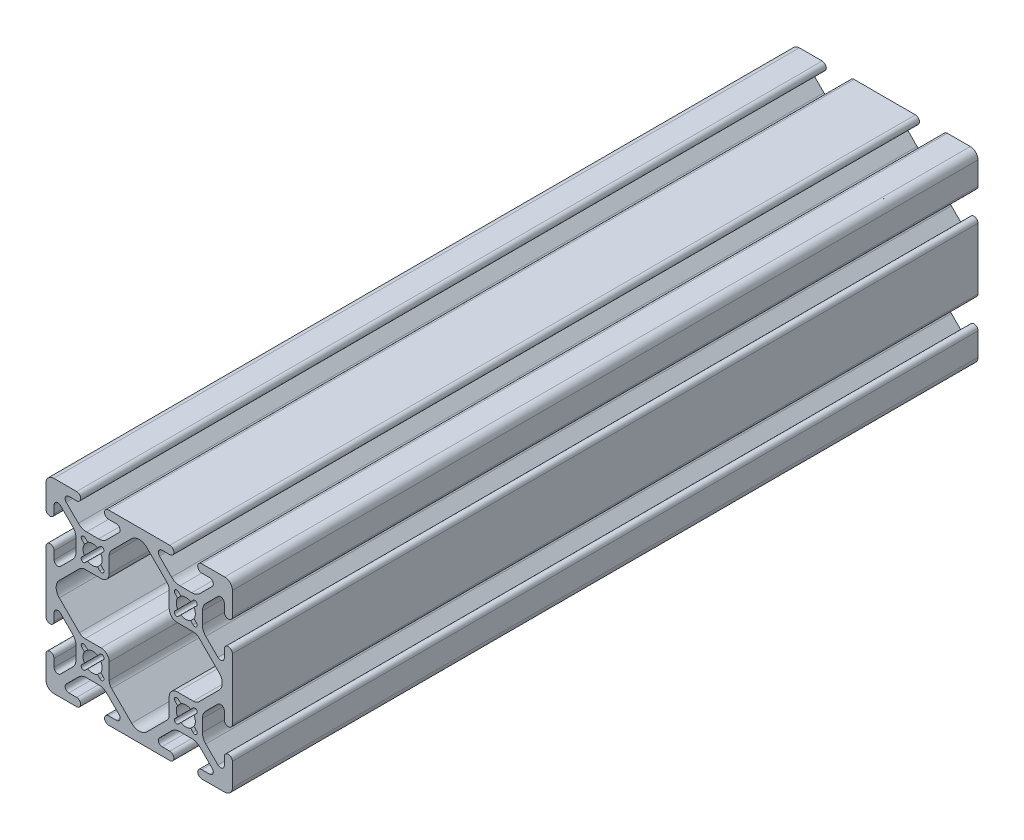
SolidWorks part; units mm, degrees
material "6105-T5 Aluminum"
ref_plane "Front Plane" through (0, 0, 0) normal (0, 0, 1) x (1, 0, 0)
ref_plane "Top Plane" through (0, 0, 0) normal (0, 1, 0) x (1, 0, 0)
ref_plane "Right Plane" through (0, 0, 0) normal (1, 0, 0) x (0, 0, -1)
sketch "Sketch1" plane through (0, 0, 0) normal (0, 0, 1) x (1, 0, 0)
  line L0 (-14.6692, 15.5605) -> (-14.0405, 14.9319)
  line L1 (-11.3595, 14.9319) -> (-10.7308, 15.5605)
  line L2 (-9.8395, 14.6692) -> (-10.4681, 14.0405)
  line L3 (-10.4681, 11.3595) -> (-9.8395, 10.7308)
  line L4 (-10.7308, 9.8395) -> (-11.3595, 10.4681)
  line L5 (-14.0405, 10.4681) -> (-14.6692, 9.8395)
  line L6 (-15.5605, 10.7308) -> (-14.9319, 11.3595)
  line L7 (-14.9319, 14.0405) -> (-15.5605, 14.6692)
  line L8 (11.3595, 10.4681) -> (10.7308, 9.8395)
  line L9 (9.8395, 10.7308) -> (10.4681, 11.3595)
  line L10 (10.4681, 14.0405) -> (9.8395, 14.6692)
  line L11 (10.7308, 15.5605) -> (11.3595, 14.9319)
  line L12 (14.0405, 14.9319) -> (14.6692, 15.5605)
  line L13 (15.5605, 14.6692) -> (14.9319, 14.0405)
  line L14 (14.9319, 11.3595) -> (15.5605, 10.7308)
  line L15 (14.6692, 9.8395) -> (14.0405, 10.4681)
  line L16 (-14.6692, -9.8395) -> (-14.0405, -10.4681)
  line L17 (-11.3595, -10.4681) -> (-10.7308, -9.8395)
  line L18 (-9.8395, -10.7308) -> (-10.4681, -11.3595)
  line L19 (-10.4681, -14.0405) -> (-9.8395, -14.6692)
  line L20 (-10.7308, -15.5605) -> (-11.3595, -14.9319)
  line L21 (-14.0405, -14.9319) -> (-14.6692, -15.5605)
  line L22 (-15.5605, -14.6692) -> (-14.9319, -14.0405)
  line L23 (-14.9319, -11.3595) -> (-15.5605, -10.7308)
  line L24 (10.7308, -9.8395) -> (11.3595, -10.4681)
  line L25 (14.0405, -10.4681) -> (14.6692, -9.8395)
  line L26 (15.5605, -10.7308) -> (14.9319, -11.3595)
  line L27 (14.9319, -14.0405) -> (15.5605, -14.6692)
  line L28 (14.6692, -15.5605) -> (14.0405, -14.9319)
  line L29 (11.3595, -14.9319) -> (10.7308, -15.5605)
  line L30 (9.8395, -14.6692) -> (10.4681, -14.0405)
  line L31 (10.4681, -11.3595) -> (9.8395, -10.7308)
  line L32 (7.5356, -16.3017) -> (2.0587, -21.7787)
  line L33 (-2.0587, -21.7787) -> (-7.5356, -16.3017)
  line L34 (-8.1828, -14.7392) -> (-8.1828, -10.3926)
  line L35 (-10.3926, -8.1828) -> (-14.7392, -8.1828)
  line L36 (-16.3017, -7.5356) -> (-21.7787, -2.0587)
  line L37 (-21.7787, 2.0587) -> (-16.3017, 7.5356)
  line L38 (-14.7392, 8.1828) -> (-10.3926, 8.1828)
  line L39 (-8.1828, 10.3926) -> (-8.1828, 14.7392)
  line L40 (-7.5356, 16.3017) -> (-2.0587, 21.7787)
  line L41 (2.0587, 21.7787) -> (7.5356, 16.3017)
  line L42 (8.1828, 14.7392) -> (8.1828, 10.3926)
  line L43 (10.3926, 8.1828) -> (14.7392, 8.1828)
  line L44 (16.3017, 7.5356) -> (21.7787, 2.0587)
  line L45 (21.7787, -2.0587) -> (16.3017, -7.5356)
  line L46 (14.7392, -8.1828) -> (10.3926, -8.1828)
  line L47 (8.1828, -10.3926) -> (8.1828, -14.7392)
  line L48 (25.4, 17.0561) -> (25.4, 23.2918)
  line L49 (23.2918, 25.4) -> (17.0561, 25.4)
  line L50 (17.0561, 23.1902) -> (19.1749, 23.1902)
  line L51 (19.8933, 21.4558) -> (16.5846, 18.1471)
  line L52 (14.3396, 17.2172) -> (11.0604, 17.2172)
  line L53 (8.8154, 18.1471) -> (5.5067, 21.4558)
  line L54 (6.2251, 23.1902) -> (8.3439, 23.1902)
  line L55 (8.3439, 25.4) -> (-8.3439, 25.4)
  line L56 (-8.3439, 23.1902) -> (-6.2251, 23.1902)
  line L57 (-5.5067, 21.4558) -> (-8.8154, 18.1471)
  line L58 (-11.0604, 17.2172) -> (-14.3396, 17.2172)
  line L59 (-16.5846, 18.1471) -> (-19.8933, 21.4558)
  line L60 (-19.1749, 23.1902) -> (-17.0561, 23.1902)
  line L61 (-17.0561, 25.4) -> (-23.2918, 25.4)
  line L62 (-25.4, 23.2918) -> (-25.4, 17.0561)
  line L63 (-23.1902, 17.0561) -> (-23.1902, 19.1749)
  line L64 (-21.4558, 19.8933) -> (-18.1471, 16.5846)
  line L65 (-17.2172, 14.3396) -> (-17.2172, 11.0604)
  line L66 (-18.1471, 8.8154) -> (-21.4558, 5.5067)
  line L67 (-23.1902, 6.2251) -> (-23.1902, 8.3439)
  line L68 (-25.4, 8.3439) -> (-25.4, -8.3439)
  line L69 (-23.1902, -8.3439) -> (-23.1902, -6.2251)
  line L70 (-21.4558, -5.5067) -> (-18.1471, -8.8154)
  line L71 (-17.2172, -11.0604) -> (-17.2172, -14.3396)
  line L72 (-18.1471, -16.5846) -> (-21.4558, -19.8933)
  line L73 (-23.1902, -19.1749) -> (-23.1902, -17.0561)
  line L74 (-25.4, -17.0561) -> (-25.4, -23.2918)
  line L75 (-23.2918, -25.4) -> (-17.0561, -25.4)
  line L76 (-17.0561, -23.1902) -> (-19.1749, -23.1902)
  line L77 (-19.8933, -21.4558) -> (-16.5846, -18.1471)
  line L78 (-14.3396, -17.2172) -> (-11.0604, -17.2172)
  line L79 (-8.8154, -18.1471) -> (-5.5067, -21.4558)
  line L80 (-6.2251, -23.1902) -> (-8.3439, -23.1902)
  line L81 (-8.3439, -25.4) -> (8.3439, -25.4)
  line L82 (8.3439, -23.1902) -> (6.2251, -23.1902)
  line L83 (5.5067, -21.4558) -> (8.8154, -18.1471)
  line L84 (11.0604, -17.2172) -> (14.3396, -17.2172)
  line L85 (16.5846, -18.1471) -> (19.8933, -21.4558)
  line L86 (19.1749, -23.1902) -> (17.0561, -23.1902)
  line L87 (17.0561, -25.4) -> (23.2918, -25.4)
  line L88 (25.4, -23.2918) -> (25.4, -17.0561)
  line L89 (23.1902, -17.0561) -> (23.1902, -19.1749)
  line L90 (21.4558, -19.8933) -> (18.1471, -16.5846)
  line L91 (17.2172, -14.3396) -> (17.2172, -11.0604)
  line L92 (18.1471, -8.8154) -> (21.4558, -5.5067)
  line L93 (23.1902, -6.2251) -> (23.1902, -8.3439)
  line L94 (25.4, -8.3439) -> (25.4, 8.3439)
  line L95 (23.1902, 8.3439) -> (23.1902, 6.2251)
  line L96 (21.4558, 5.5067) -> (18.1471, 8.8154)
  line L97 (17.2172, 11.0604) -> (17.2172, 14.3396)
  line L98 (18.1471, 16.5846) -> (21.4558, 19.8933)
  line L99 (23.1902, 19.1749) -> (23.1902, 17.0561)
  arc A0 (-11.3595, 14.9319) -> (-14.0405, 14.9319) centre (-12.7, 12.7) ccw
  arc A1 (-9.8395, 14.6692) -> (-10.7308, 15.5605) centre (-10.2304, 15.1696) ccw
  arc A2 (-10.4681, 11.3595) -> (-10.4681, 14.0405) centre (-12.7, 12.7) ccw
  arc A3 (-10.7308, 9.8395) -> (-9.8395, 10.7308) centre (-10.2304, 10.2304) ccw
  arc A4 (-14.0405, 10.4681) -> (-11.3595, 10.4681) centre (-12.7, 12.7) ccw
  arc A5 (-15.5605, 10.7308) -> (-14.6692, 9.8395) centre (-15.1696, 10.2304) ccw
  arc A6 (-14.9319, 14.0405) -> (-14.9319, 11.3595) centre (-12.7, 12.7) ccw
  arc A7 (-14.6692, 15.5605) -> (-15.5605, 14.6692) centre (-15.1696, 15.1696) ccw
  arc A8 (9.8395, 10.7308) -> (10.7308, 9.8395) centre (10.2304, 10.2304) ccw
  arc A9 (10.4681, 14.0405) -> (10.4681, 11.3595) centre (12.7, 12.7) ccw
  arc A10 (10.7308, 15.5605) -> (9.8395, 14.6692) centre (10.2304, 15.1696) ccw
  arc A11 (14.0405, 14.9319) -> (11.3595, 14.9319) centre (12.7, 12.7) ccw
  arc A12 (15.5605, 14.6692) -> (14.6692, 15.5605) centre (15.1696, 15.1696) ccw
  arc A13 (14.9319, 11.3595) -> (14.9319, 14.0405) centre (12.7, 12.7) ccw
  arc A14 (14.6692, 9.8395) -> (15.5605, 10.7308) centre (15.1696, 10.2304) ccw
  arc A15 (11.3595, 10.4681) -> (14.0405, 10.4681) centre (12.7, 12.7) ccw
  arc A16 (-11.3595, -10.4681) -> (-14.0405, -10.4681) centre (-12.7, -12.7) ccw
  arc A17 (-9.8395, -10.7308) -> (-10.7308, -9.8395) centre (-10.2304, -10.2304) ccw
  arc A18 (-10.4681, -14.0405) -> (-10.4681, -11.3595) centre (-12.7, -12.7) ccw
  arc A19 (-10.7308, -15.5605) -> (-9.8395, -14.6692) centre (-10.2304, -15.1696) ccw
  arc A20 (-14.0405, -14.9319) -> (-11.3595, -14.9319) centre (-12.7, -12.7) ccw
  arc A21 (-15.5605, -14.6692) -> (-14.6692, -15.5605) centre (-15.1696, -15.1696) ccw
  arc A22 (-14.9319, -11.3595) -> (-14.9319, -14.0405) centre (-12.7, -12.7) ccw
  arc A23 (-14.6692, -9.8395) -> (-15.5605, -10.7308) centre (-15.1696, -10.2304) ccw
  arc A24 (14.0405, -10.4681) -> (11.3595, -10.4681) centre (12.7, -12.7) ccw
  arc A25 (15.5605, -10.7308) -> (14.6692, -9.8395) centre (15.1696, -10.2304) ccw
  arc A26 (14.9319, -14.0405) -> (14.9319, -11.3595) centre (12.7, -12.7) ccw
  arc A27 (14.6692, -15.5605) -> (15.5605, -14.6692) centre (15.1696, -15.1696) ccw
  arc A28 (11.3595, -14.9319) -> (14.0405, -14.9319) centre (12.7, -12.7) ccw
  arc A29 (9.8395, -14.6692) -> (10.7308, -15.5605) centre (10.2304, -15.1696) ccw
  arc A30 (10.4681, -11.3595) -> (10.4681, -14.0405) centre (12.7, -12.7) ccw
  arc A31 (10.7308, -9.8395) -> (9.8395, -10.7308) centre (10.2304, -10.2304) ccw
  arc A32 (-2.0587, -21.7787) -> (2.0587, -21.7787) centre (0, -19.72) ccw
  arc A33 (-8.1828, -14.7392) -> (-7.5356, -16.3017) centre (-5.973, -14.7392) ccw
  arc A34 (-8.1828, -10.3926) -> (-10.3926, -8.1828) centre (-10.3926, -10.3926) ccw
  arc A35 (-16.3017, -7.5356) -> (-14.7392, -8.1828) centre (-14.7392, -5.973) ccw
  arc A36 (-21.7787, 2.0587) -> (-21.7787, -2.0587) centre (-19.72, 0) ccw
  arc A37 (-14.7392, 8.1828) -> (-16.3017, 7.5356) centre (-14.7392, 5.973) ccw
  arc A38 (-10.3926, 8.1828) -> (-8.1828, 10.3926) centre (-10.3926, 10.3926) ccw
  arc A39 (-7.5356, 16.3017) -> (-8.1828, 14.7392) centre (-5.973, 14.7392) ccw
  arc A40 (2.0587, 21.7787) -> (-2.0587, 21.7787) centre (0, 19.72) ccw
  arc A41 (8.1828, 14.7392) -> (7.5356, 16.3017) centre (5.973, 14.7392) ccw
  arc A42 (8.1828, 10.3926) -> (10.3926, 8.1828) centre (10.3926, 10.3926) ccw
  arc A43 (16.3017, 7.5356) -> (14.7392, 8.1828) centre (14.7392, 5.973) ccw
  arc A44 (21.7787, -2.0587) -> (21.7787, 2.0587) centre (19.72, 0) ccw
  arc A45 (14.7392, -8.1828) -> (16.3017, -7.5356) centre (14.7392, -5.973) ccw
  arc A46 (10.3926, -8.1828) -> (8.1828, -10.3926) centre (10.3926, -10.3926) ccw
  arc A47 (7.5356, -16.3017) -> (8.1828, -14.7392) centre (5.973, -14.7392) ccw
  arc A48 (23.1902, 17.0561) -> (25.4, 17.0561) centre (24.2951, 17.0561) ccw
  arc A49 (25.4, 23.2918) -> (23.2918, 25.4) centre (23.2918, 23.2918) ccw
  arc A50 (17.0561, 25.4) -> (17.0561, 23.1902) centre (17.0561, 24.2951) ccw
  arc A51 (19.8933, 21.4558) -> (19.1749, 23.1902) centre (19.1749, 22.1742) ccw
  arc A52 (14.3396, 17.2172) -> (16.5846, 18.1471) centre (14.3396, 20.3922) ccw
  arc A53 (8.8154, 18.1471) -> (11.0604, 17.2172) centre (11.0604, 20.3922) ccw
  arc A54 (6.2251, 23.1902) -> (5.5067, 21.4558) centre (6.2251, 22.1742) ccw
  arc A55 (8.3439, 23.1902) -> (8.3439, 25.4) centre (8.3439, 24.2951) ccw
  arc A56 (-8.3439, 25.4) -> (-8.3439, 23.1902) centre (-8.3439, 24.2951) ccw
  arc A57 (-5.5067, 21.4558) -> (-6.2251, 23.1902) centre (-6.2251, 22.1742) ccw
  arc A58 (-11.0604, 17.2172) -> (-8.8154, 18.1471) centre (-11.0604, 20.3922) ccw
  arc A59 (-16.5846, 18.1471) -> (-14.3396, 17.2172) centre (-14.3396, 20.3922) ccw
  arc A60 (-19.1749, 23.1902) -> (-19.8933, 21.4558) centre (-19.1749, 22.1742) ccw
  arc A61 (-17.0561, 23.1902) -> (-17.0561, 25.4) centre (-17.0561, 24.2951) ccw
  arc A62 (-23.2918, 25.4) -> (-25.4, 23.2918) centre (-23.2918, 23.2918) ccw
  arc A63 (-25.4, 17.0561) -> (-23.1902, 17.0561) centre (-24.2951, 17.0561) ccw
  arc A64 (-21.4558, 19.8933) -> (-23.1902, 19.1749) centre (-22.1742, 19.1749) ccw
  arc A65 (-17.2172, 14.3396) -> (-18.1471, 16.5846) centre (-20.3922, 14.3396) ccw
  arc A66 (-18.1471, 8.8154) -> (-17.2172, 11.0604) centre (-20.3922, 11.0604) ccw
  arc A67 (-23.1902, 6.2251) -> (-21.4558, 5.5067) centre (-22.1742, 6.2251) ccw
  arc A68 (-23.1902, 8.3439) -> (-25.4, 8.3439) centre (-24.2951, 8.3439) ccw
  arc A69 (-25.4, -8.3439) -> (-23.1902, -8.3439) centre (-24.2951, -8.3439) ccw
  arc A70 (-21.4558, -5.5067) -> (-23.1902, -6.2251) centre (-22.1742, -6.2251) ccw
  arc A71 (-17.2172, -11.0604) -> (-18.1471, -8.8154) centre (-20.3922, -11.0604) ccw
  arc A72 (-18.1471, -16.5846) -> (-17.2172, -14.3396) centre (-20.3922, -14.3396) ccw
  arc A73 (-23.1902, -19.1749) -> (-21.4558, -19.8933) centre (-22.1742, -19.1749) ccw
  arc A74 (-23.1902, -17.0561) -> (-25.4, -17.0561) centre (-24.2951, -17.0561) ccw
  arc A75 (-25.4, -23.2918) -> (-23.2918, -25.4) centre (-23.2918, -23.2918) ccw
  arc A76 (-17.0561, -25.4) -> (-17.0561, -23.1902) centre (-17.0561, -24.2951) ccw
  arc A77 (-19.8933, -21.4558) -> (-19.1749, -23.1902) centre (-19.1749, -22.1742) ccw
  arc A78 (-14.3396, -17.2172) -> (-16.5846, -18.1471) centre (-14.3396, -20.3922) ccw
  arc A79 (-8.8154, -18.1471) -> (-11.0604, -17.2172) centre (-11.0604, -20.3922) ccw
  arc A80 (-6.2251, -23.1902) -> (-5.5067, -21.4558) centre (-6.2251, -22.1742) ccw
  arc A81 (-8.3439, -23.1902) -> (-8.3439, -25.4) centre (-8.3439, -24.2951) ccw
  arc A82 (8.3439, -25.4) -> (8.3439, -23.1902) centre (8.3439, -24.2951) ccw
  arc A83 (5.5067, -21.4558) -> (6.2251, -23.1902) centre (6.2251, -22.1742) ccw
  arc A84 (11.0604, -17.2172) -> (8.8154, -18.1471) centre (11.0604, -20.3922) ccw
  arc A85 (16.5846, -18.1471) -> (14.3396, -17.2172) centre (14.3396, -20.3922) ccw
  arc A86 (19.1749, -23.1902) -> (19.8933, -21.4558) centre (19.1749, -22.1742) ccw
  arc A87 (17.0561, -23.1902) -> (17.0561, -25.4) centre (17.0561, -24.2951) ccw
  arc A88 (23.2918, -25.4) -> (25.4, -23.2918) centre (23.2918, -23.2918) ccw
  arc A89 (25.4, -17.0561) -> (23.1902, -17.0561) centre (24.2951, -17.0561) ccw
  arc A90 (21.4558, -19.8933) -> (23.1902, -19.1749) centre (22.1742, -19.1749) ccw
  arc A91 (17.2172, -14.3396) -> (18.1471, -16.5846) centre (20.3922, -14.3396) ccw
  arc A92 (18.1471, -8.8154) -> (17.2172, -11.0604) centre (20.3922, -11.0604) ccw
  arc A93 (23.1902, -6.2251) -> (21.4558, -5.5067) centre (22.1742, -6.2251) ccw
  arc A94 (23.1902, -8.3439) -> (25.4, -8.3439) centre (24.2951, -8.3439) ccw
  arc A95 (25.4, 8.3439) -> (23.1902, 8.3439) centre (24.2951, 8.3439) ccw
  arc A96 (21.4558, 5.5067) -> (23.1902, 6.2251) centre (22.1742, 6.2251) ccw
  arc A97 (17.2172, 11.0604) -> (18.1471, 8.8154) centre (20.3922, 11.0604) ccw
  arc A98 (18.1471, 16.5846) -> (17.2172, 14.3396) centre (20.3922, 14.3396) ccw
  arc A99 (23.1902, 19.1749) -> (21.4558, 19.8933) centre (22.1742, 19.1749) ccw
extrude "Extrude1" add sketch "Sketch1" against normal blind 203.2
